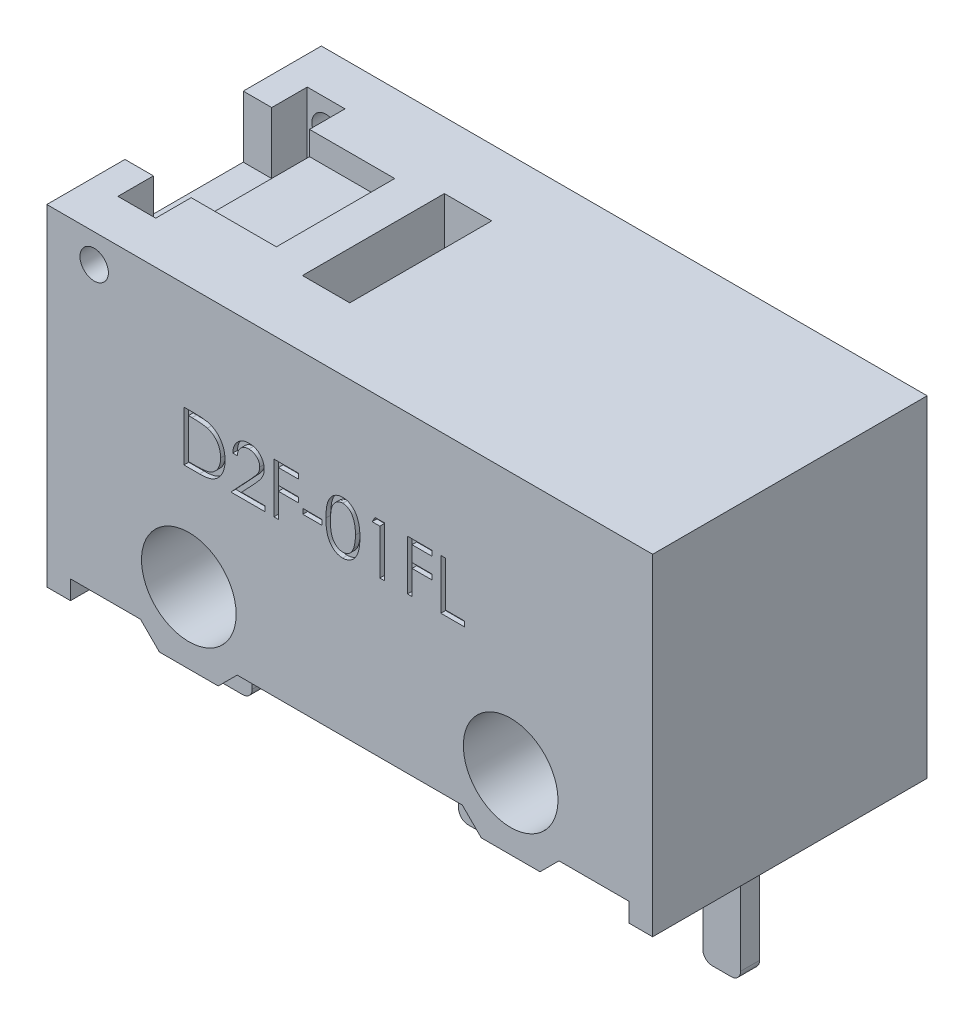
SolidWorks part; units mm, degrees
ref_plane "Front Plane" through (0, 0, 0) normal (0, 0, 1) x (1, 0, 0)
ref_plane "Top Plane" through (0, 0, 0) normal (0, 1, 0) x (1, 0, 0)
ref_plane "Right Plane" through (0, 0, 0) normal (1, 0, 0) x (0, 0, -1)
sketch "Sketch1" plane through (0, 0, 0) normal (0, 0, 1) x (1, 0, 0)
  line L0 (-2.7787, -3.5) -> (-2.3787, -3.1)
  line L1 (6.4, -3.5) -> (5.9, -3.5)
  line L2 (6.4, -3.5) -> (6.4, 3.5)
  line L3 (6.4, 3.5) -> (-6.4, 3.5)
  line L4 (-6.4, -3.5) -> (-6.4, 3.5)
  line L5 (6.4, -3.5) -> (-6.4, 3.5) construction
  line L6 (6.4, 3.5) -> (-6.4, -3.5) construction
  line L7 (-2.3787, -3.1) -> (2.3787, -3.1)
  line L8 (2.3787, -3.1) -> (2.7787, -3.5)
  line L9 (5.9, -3.5) -> (5.9, -3.1)
  line L10 (5.9, -3.1) -> (4.4205, -3.1)
  line L11 (4.4205, -3.1) -> (4.0205, -3.5)
  line L12 (-5.9, -3.5) -> (-5.9, -3.1)
  line L13 (-5.9, -3.1) -> (-4.4213, -3.1)
  line L14 (-4.4213, -3.1) -> (-4.0213, -3.5)
  line L15 (-5.9, -3.5) -> (-6.4, -3.5)
  line L16 (-2.7787, -3.5) -> (-4.0213, -3.5)
  line L17 (4.0205, -3.5) -> (2.7787, -3.5)
  circle A0 centre (3.4, -2) radius 1
  circle A1 centre (-3.4, -2) radius 1
  point P0 (0, 0)
  dimension "D6" = 2
  dimension "D7" = 2
  dimension "D13" = 1.5
  dimension "D1" = 12.8
  dimension "D2" = 7
  dimension "D3" = 3
  dimension "D4" = 3
  dimension "D5" = 1.5
  dimension "D8" = 0.5
  dimension "D9" = 0.5
  dimension "D10" = 45
  dimension "D11" = 45
  dimension "D12" = 45
  dimension "D14" = 1.5
  dimension "D15" = 1.5
  dimension "D16" = 1.4994
  dimension "D17" = 0.4
  dimension "D18" = 0.4
  dimension "D19" = 0.4
  dimension "D20" = 45
extrude "Boss-Extrude1" add sketch "Sketch1" along normal blind 5.8
sketch "Sketch2" plane through (0, 3.5, 0) normal (0, 1, 0) x (1, 0, 0)
  line L0 (-6.4, -1.65) -> (-5.798, -1.65)
  line L2 (-6.4, -5.8) -> (-6.4, 0) construction
  line L3 (-5.798, -1.65) -> (-5.798, -0.9)
  line L4 (-5.798, -0.9) -> (-5, -0.9)
  line L5 (-5, -0.9) -> (-5, -4.9)
  line L6 (-5, -4.9) -> (-5.798, -4.9)
  line L7 (-5.798, -4.9) -> (-5.798, -4.15)
  line L8 (-5.798, -4.15) -> (-6.4, -4.15)
  line L9 (-6.4, -1.65) -> (-6.4, -4.15)
  point P4 (-6.4, -2.9)
  point P11 (-6.4, -2.9)
  point P12 (-6.4, -2.9)
  point P13 (-6.4, -2.9)
  dimension "D1" = 1.25
  dimension "D2" = 1.25
  dimension "D3" = 1.4
  dimension "D4" = 0.798
  dimension "D5" = 0.798
  dimension "D6" = 2
  dimension "D7" = 2
extrude "Cut-Extrude1" cut sketch "Sketch2" against normal blind 1.3
sketch "Sketch3" plane through (0, 3.5, 0) normal (0, 1, 0) x (1, 0, 0)
  line L0 (-5, -1.65) -> (-3.2, -1.65)
  line L1 (-5, -4.9) -> (-5, -0.9) construction
  line L2 (-3.2, -1.65) -> (-3.2, -4.15)
  line L3 (-3.2, -4.15) -> (-5, -4.15)
  line L4 (-5, -4.9) -> (-5, -0.9) construction
  line L6 (-5, -1.65) -> (-5, -4.15)
  point P4 (-5, -2.9)
  point P10 (-5, -2.9)
  dimension "D1" = 1.25
  dimension "D2" = 1.25
  dimension "D3" = 3.2
extrude "Cut-Extrude2" cut sketch "Sketch3" against normal blind 0.5
sketch "Sketch4" plane through (0, 3.5, 0) normal (0, 1, 0) x (1, 0, 0)
  line L1 (-2.4, -1.4) -> (-1.4, -1.4)
  line L2 (-2.4, -1.4) -> (-2.4, -4.4)
  line L3 (-2.4, -4.4) -> (-1.4, -4.4)
  line L4 (-1.4, -1.4) -> (-1.4, -4.4)
  line L6 (6.4, 0) -> (-6.4, 0) construction
  line L7 (-6.4, -5.8) -> (-6.4, -4.15) construction
  dimension "D1" = 1
  dimension "D2" = 3
  dimension "D3" = 1.4
  dimension "D4" = 4
extrude "Cut-Extrude3" cut sketch "Sketch4" against normal blind 2
sketch "Sketch5" plane through (0, 0, 5.8) normal (0, 0, 1) x (1, 0, 0)
  line L0 (-6.4, 3.5) -> (-6.4, -3.5) construction
  line L1 (6.4, 3.5) -> (-6.4, 3.5) construction
  circle A0 centre (-5.4, 2.9) radius 0.3
  dimension "D3" = 0.6
  dimension "D1" = 1
  dimension "D2" = 0.6
extrude "Cut-Extrude4" cut sketch "Sketch5" against normal through all
sketch "Sketch6" plane through (0, -3.1, 0) normal (0, -1, 0) x (1, 0, 0)
  line L0 (6.4, 5.8) -> (6.4, 0) construction
  line L1 (-0.4, 3.1) -> (0.4, 3.1)
  line L2 (-0.4, 3.1) -> (-0.4, 2.7)
  line L3 (-0.4, 2.7) -> (0.4, 2.7)
  line L4 (0.4, 3.1) -> (0.4, 2.7)
  line L5 (-0.4, 3.1) -> (0.4, 2.7) construction
  line L6 (-0.4, 2.7) -> (0.4, 3.1) construction
  line L7 (4.76, 3.1) -> (5.56, 3.1)
  line L8 (4.76, 3.1) -> (4.76, 2.7)
  line L9 (4.76, 2.7) -> (5.56, 2.7)
  line L10 (5.56, 3.1) -> (5.56, 2.7)
  line L11 (4.76, 3.1) -> (5.56, 2.7) construction
  line L12 (4.76, 2.7) -> (5.56, 3.1) construction
  line L13 (-5.56, 3.1) -> (-4.76, 3.1)
  line L14 (-5.56, 3.1) -> (-5.56, 2.7)
  line L15 (-5.56, 2.7) -> (-4.76, 2.7)
  line L16 (-4.76, 3.1) -> (-4.76, 2.7)
  line L17 (-5.56, 3.1) -> (-4.76, 2.7) construction
  line L18 (-5.56, 2.7) -> (-4.76, 3.1) construction
  line L19 (-2.3787, 5.8) -> (2.3787, 5.8) construction
  line L20 (-6.4, 5.8) -> (-6.4, 0) construction
  line L21 (4.4205, 5.8) -> (5.9, 5.8) construction
  line L22 (-5.9, 5.8) -> (-4.4213, 5.8) construction
  point P0 (0, 2.9)
  point P5 (5.16, 2.9)
  point P10 (-5.16, 2.9)
  dimension "D1" = 0.8
  dimension "D2" = 0.4
  dimension "D3" = 0.8
  dimension "D4" = 0.4
  dimension "D5" = 0.8
  dimension "D6" = 0.4
  dimension "D7" = 6.4
  dimension "D8" = 2.9
  dimension "D9" = 1.24
  dimension "D10" = 1.24
  dimension "D11" = 2.9
  dimension "D12" = 2.9
extrude "Boss-Extrude2" add sketch "Sketch6" along normal blind 3
fillet "Fillet1" radius 0.2 6 edges at (0.4, -6.1, 2.9) (-0.4, -6.1, 2.9) (-5.56, -6.1, 2.9) (-4.76, -6.1, 2.9) (4.76, -6.1, 2.9) (5.56, -6.1, 2.9)
sketch "Sketch7" plane through (0, 0, 5.8) normal (0, 0, 1) x (1, 0, 0)
  text T0 "D2F-01FL" font "Century Gothic" height in points 4
extrude "Cut-Extrude5" cut sketch "Sketch7" against normal blind 0.1
